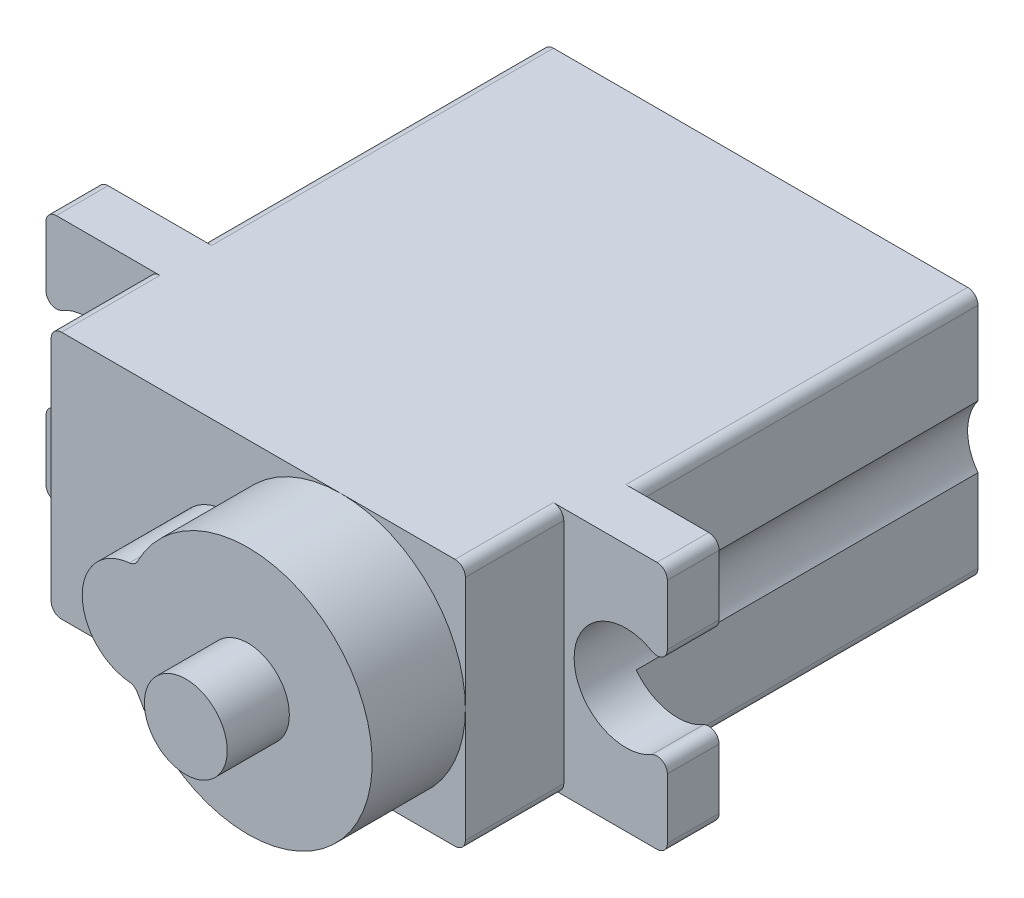
SolidWorks part; units mm, degrees
ref_plane "Front Plane" through (0, 0, 0) normal (1, 0, 0) x (0, 1, 0)
ref_plane "Top Plane" through (0, 0, 0) normal (0, 0, 1) x (0, 1, 0)
ref_plane "Right Plane" through (0, 0, 0) normal (0, 1, 0) x (-1, 0, 0)
sketch "Sketch1" plane through (0, 0, 0) normal (0, 0, 1) x (0, 1, 0)
  line L1 (6.9751, 7.3881) -> (-5.0249, 7.3881)
  line L2 (6.9751, 7.3881) -> (6.9751, -13.6119)
  line L3 (6.9751, -13.6119) -> (-5.0249, -13.6119)
  line L4 (-5.0249, 7.3881) -> (-5.0249, -13.6119)
  dimension "D1" = 21
  dimension "D2" = 12
extrude "Boss-Extrude1" add sketch "Sketch1" along normal blind 16.5
sketch "Sketch2" plane through (0, 0, 16.5) normal (0, 0, 1) x (1, 0, 0)
  line L0 (-7.3881, 6.9751) -> (-12.3881, 6.9751)
  line L1 (-7.3881, 6.9751) -> (12.6119, 6.9751)
  line L3 (-7.3881, -5.0249) -> (13.6119, -5.0249)
  line L5 (-12.3881, 6.9751) -> (-12.3881, -5.0249)
  line L6 (-12.3881, -5.0249) -> (-7.3881, -5.0249)
  line L7 (12.6119, 6.9751) -> (17.6119, 6.9751)
  line L8 (17.6119, 6.9751) -> (17.6119, -5.0249)
  line L9 (17.6119, -5.0249) -> (13.6119, -5.0249)
  dimension "D1" = 5
  dimension "D2" = 5
extrude "Boss-Extrude2" add sketch "Sketch2" along normal blind 2.5
sketch "Sketch3" plane through (0, 0, 19) normal (0, 0, 1) x (1, 0, 0)
  line L0 (-12.3881, -5.0249) -> (17.6119, -5.0249) construction
  line L1 (-7.3881, -5.0249) -> (12.6119, -5.0249)
  line L2 (-7.3881, -5.0249) -> (-7.3881, 6.9751)
  line L3 (-7.3881, 6.9751) -> (12.6119, 6.9751)
  line L4 (12.6119, -5.0249) -> (12.6119, 6.9751)
  line L5 (17.6119, 6.9751) -> (-12.3881, 6.9751) construction
  line L6 (-12.3881, 6.9751) -> (-12.3881, -5.0249) construction
  line L7 (17.6119, 6.9751) -> (17.6119, -5.0249) construction
  dimension "D1" = 5
  dimension "D2" = 5
extrude "Boss-Extrude3" add sketch "Sketch3" along normal blind 4.75
sketch "Sketch4" plane through (0, 0, 23.75) normal (0, 0, 1) x (1, 0, 0)
  line L0 (12.6119, -5.0249) -> (12.6119, 6.9751) construction
  line L1 (12.6119, 6.9751) -> (-7.3881, 6.9751) construction
  arc A0 (1.1574, -1.5245) -> (1.1574, 3.4747) centre (6.6119, 0.9751) ccw
  arc A3 (1.1574, 3.4747) -> (1.1574, -1.5245) centre (1.1119, 0.9751) ccw
  point P1 (7.1119, 0.9751)
  dimension "D1" = 12
  dimension "D2" = 6
  dimension "D3" = 5
  dimension "D4" = 5.5
extrude "Boss-Extrude4" add sketch "Sketch4" along normal blind 4.5
sketch "Sketch5" plane through (0, 0, 28.25) normal (0, 0, 1) x (1, 0, 0)
  circle A0 centre (6.6119, 0.9751) radius 2
  dimension "D1" = 4
extrude "Boss-Extrude5" add sketch "Sketch5" along normal blind 3 separate body
sketch "Sketch7" plane through (0, 0, 19) normal (0, 0, 1) x (1, 0, 0)
  line L0 (-7.3881, 6.9751) -> (-7.3881, -5.0249) construction
  line L1 (12.6119, -5.0249) -> (12.6119, 6.9751) construction
  line L2 (-7.3881, 6.9751) -> (-12.3881, 6.9751) construction
  circle A0 centre (15.6119, 0.9751) radius 2.5
  circle A1 centre (-10.3881, 0.9751) radius 2.5
  dimension "D1" = 5
  dimension "D2" = 5
  dimension "D3" = 3
  dimension "D4" = 3
  dimension "D5" = 6
  dimension "D6" = 6
extrude "Cut-Extrude1" cut sketch "Sketch7" against normal up to next
fillet "Fillet1" radius 0.5 18 edges at (1.1574, 3.4747, 26) (1.1574, -1.5245, 26) (-12.3881, 2.4751, 17.75) (-12.3881, -0.5249, 17.75) (-12.3881, 6.9751, 17.75) (-7.3881, 6.9751, 21.375) (-7.3881, 6.9751, 8.25) (13.6119, 6.9751, 8.25) (12.6119, 6.9751, 21.375) (17.6119, 6.9751, 17.75) (17.6119, -0.5249, 17.75) (17.6119, 2.4751, 17.75) (17.6119, -5.0249, 17.75) (12.6119, -5.0249, 21.375) (-7.3881, -5.0249, 8.25) (-7.3881, -5.0249, 21.375) (-12.3881, -5.0249, 17.75) (13.6119, -5.0249, 8.25)
